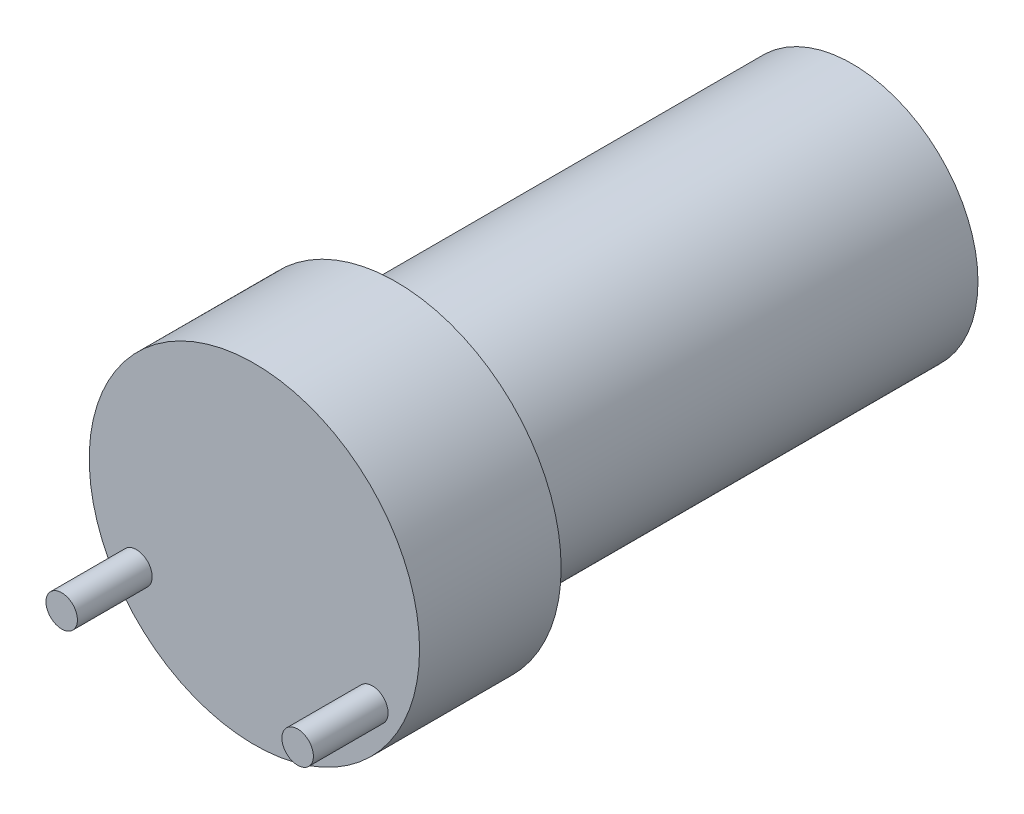
SolidWorks part; units mm, degrees
ref_plane "Plan de face" through (0, 0, 0) normal (0, 0, 1) x (1, 0, 0)
ref_plane "Plan de dessus" through (0, 0, 0) normal (0, 1, 0) x (1, 0, 0)
ref_plane "Plan de droite" through (0, 0, 0) normal (1, 0, 0) x (0, 0, -1)
sketch "Esquisse1" plane through (0, 0, 0) normal (0, 0, 1) x (1, 0, 0)
  circle A0 centre (0, 0) radius 21
extrude "Boss.-Extru.1" add sketch "Esquisse1" along normal blind 18
sketch "Esquisse2" plane through (0, 0, 0) normal (0, 0, -1) x (-1, 0, 0)
  circle A0 centre (0, 0) radius 16
extrude "Boss.-Extru.2" add sketch "Esquisse2" along normal blind 58
sketch "Esquisse7" plane through (0, 0, 18) normal (0, 0, 1) x (1, 0, 0)
  circle A0 centre (-15, -9) radius 2
  circle A1 centre (0, 0) radius 21 construction
  circle A2 centre (15, -9) radius 2
  dimension "D1" = 9
  dimension "D2" = 30
  dimension "D3" = 15
extrude "Boss.-Extru.3" add sketch "Esquisse7" along normal blind 9.5
